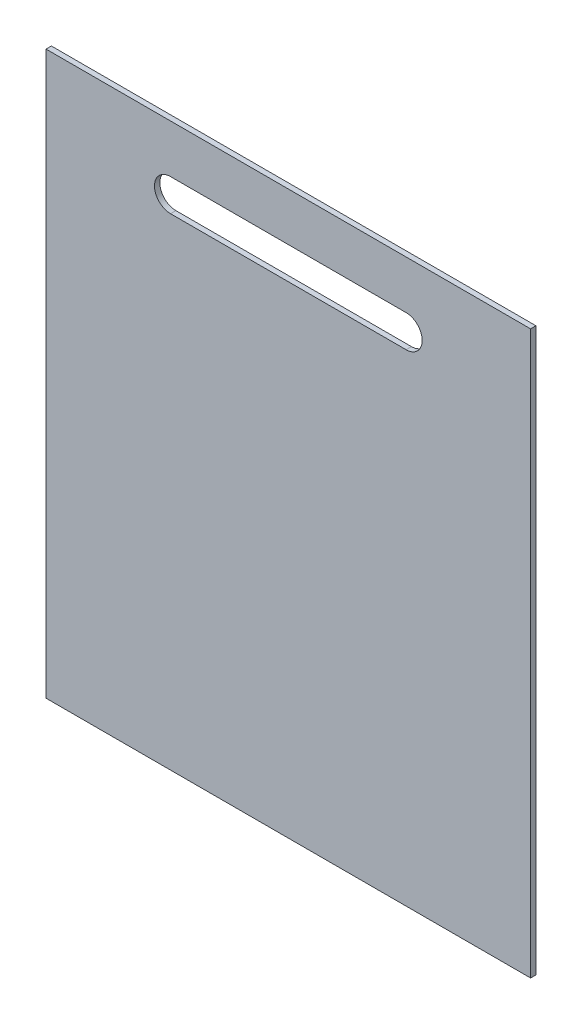
SolidWorks part; units mm, degrees
ref_plane "前视基准面" through (0, 0, 0) normal (0, 0, 1) x (1, 0, 0)
ref_plane "上视基准面" through (0, 0, 0) normal (0, 1, 0) x (1, 0, 0)
ref_plane "右视基准面" through (0, 0, 0) normal (1, 0, 0) x (0, 0, -1)
sketch "草图1" plane through (0, 0, 0) normal (0, 0, 1) x (1, 0, 0)
  line L0 (-110, 202.5) -> (110, 202.5) construction
  line L1 (-226.25, -262.5) -> (226.25, -262.5)
  line L2 (-226.25, -262.5) -> (-226.25, 262.5)
  line L3 (-226.25, 262.5) -> (226.25, 262.5)
  line L4 (226.25, -262.5) -> (226.25, 262.5)
  line L5 (-226.25, -262.5) -> (226.25, 262.5) construction
  line L6 (-226.25, 262.5) -> (226.25, -262.5) construction
  line L7 (-110, 217.5) -> (110, 217.5)
  line L8 (-110, 187.5) -> (110, 187.5)
  arc A0 (-110, 217.5) -> (-110, 187.5) centre (-110, 202.5) ccw
  arc A1 (110, 187.5) -> (110, 217.5) centre (110, 202.5) ccw
  point P0 (0, 0)
  point P8 (0, 202.5)
  point P13 (0, 0)
  point P14 (0, 0)
  dimension "D5" = 15
  dimension "D1" = 525
  dimension "D2" = 452.5
  dimension "D3" = 220
  dimension "D4" = 60
extrude "凸台-拉伸1" add sketch "草图1" along normal blind 5
